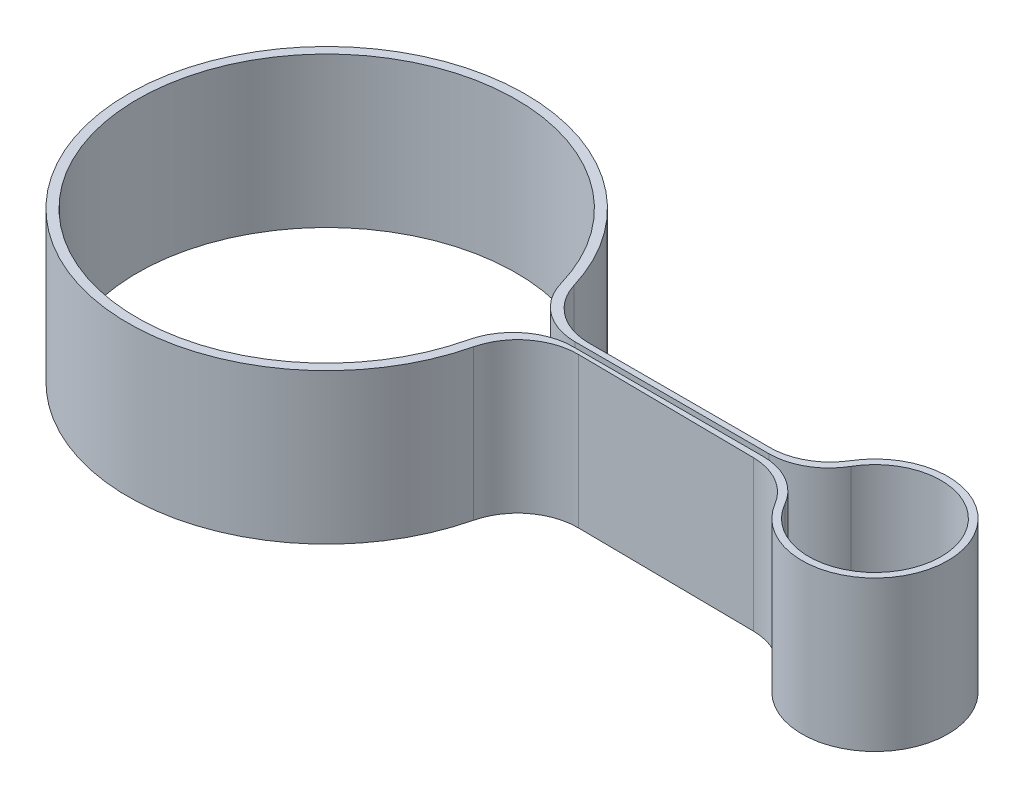
SolidWorks part; units mm, degrees
ref_plane "Спереди" through (0, 0, 0) normal (0, 0, 1) x (1, 0, 0)
ref_plane "Сверху" through (0, 0, 0) normal (0, 1, 0) x (1, 0, 0)
ref_plane "Справа" through (0, 0, 0) normal (1, 0, 0) x (0, 0, -1)
sketch "Эскиз1" plane through (0, 0, 0) normal (0, 1, 0) x (1, 0, 0)
  line L0 (67.1017, -51.5005) -> (112.3785, -51.5005)
  line L1 (65.6237, -52.4748) -> (113.435, -52.4748)
  line L3 (65.6522, -53.3443) -> (113.4286, -53.3448)
  line L5 (67.192, -53.9185) -> (112.3688, -54.3991)
  arc A0 (67.1017, -51.5005) -> (67.192, -53.9185) centre (34.1579, -53.9416) ccw
  arc A1 (112.3688, -54.3991) -> (112.3785, -51.5005) centre (124.4229, -52.9901) ccw
  circle A2 centre (34.1579, -53.9416) radius 31.5 construction
  circle A3 centre (124.4229, -52.9901) radius 11 construction
  arc A4 (65.6237, -52.4748) -> (65.6522, -53.3443) centre (34.1579, -53.9416) ccw
  arc A5 (113.4286, -53.3448) -> (113.435, -52.4748) centre (124.4229, -52.9901) ccw
extrude "Вытянуть1" add sketch "Эскиз1" along normal blind 25
fillet "Скругление1" radius 10 1 edges at (67.192, 12.5, 53.9185)
fillet "Скругление2" radius 10 1 edges at (65.6522, 12.5, 53.3443)
fillet "Скругление3" radius 10 2 edges at (67.1017, 12.5, 51.5005) (65.6237, 12.5, 52.4748)
fillet "Скругление4" radius 10 4 edges at (113.435, 12.5, 52.4748) (113.4286, 12.5, 53.3448) (112.3785, 12.5, 51.5005) (112.3688, 12.5, 54.3991)
